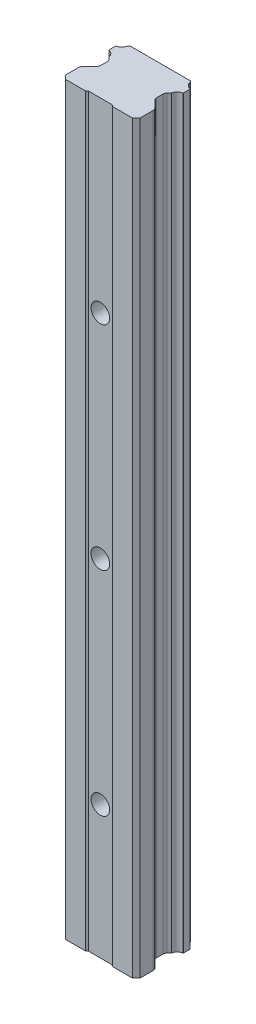
SolidWorks part; units mm, degrees
material "铸造碳钢"
ref_plane "前视基准面" through (0, 0, 0) normal (0, 0, 1) x (1, 0, 0)
ref_plane "上视基准面" through (0, 0, 0) normal (0, 1, 0) x (1, 0, 0)
ref_plane "右视基准面" through (0, 0, 0) normal (1, 0, 0) x (0, 0, -1)
sketch "草图1" plane through (0, 0, 0) normal (0, 1, 0) x (1, 0, 0)
  line L40 (11.7582, -0.4582) -> (11.3, 0)
  line L41 (11.3, 0) -> (-11.3, 0)
  line L42 (-11.3, 0) -> (-11.7582, -0.4582)
  line L43 (-14, -2.848) -> (-14, -5.152)
  line L44 (-11.7582, -7.5418) -> (-10.9393, -8.3607)
  line L45 (-10.5, -9.4213) -> (-10.5, -11.8787)
  line L46 (-10.9393, -12.9393) -> (-13.5607, -15.5607)
  line L47 (-14, -16.6213) -> (-14, -21.5)
  line L48 (-14, -21.5) -> (-12.5, -23)
  line L49 (-12.5, -23) -> (-5, -23)
  line L50 (-5, -23) -> (-4.5, -22.5)
  line L51 (-4.5, -22.5) -> (4.5, -22.5)
  line L52 (4.5, -22.5) -> (5, -23)
  line L53 (5, -23) -> (12.5, -23)
  line L54 (12.5, -23) -> (14, -21.5)
  line L55 (14, -21.5) -> (14, -16.6213)
  line L56 (13.5607, -15.5607) -> (10.9393, -12.9393)
  line L57 (10.5, -11.8787) -> (10.5, -9.4213)
  line L58 (10.9393, -8.3607) -> (11.7582, -7.5418)
  line L59 (14, -5.152) -> (14, -2.848)
  arc A36 (11.7782, -0.4802) -> (11.7582, -0.4582) centre (11.5461, -0.6703) ccw
  arc A37 (-11.7582, -0.4582) -> (-11.7782, -0.4802) centre (-11.5461, -0.6703) ccw
  arc A38 (-13.8926, -2.618) -> (-11.7782, -0.4802) centre (-14.2555, -0.1445) ccw
  arc A39 (-13.8926, -2.618) -> (-14, -2.848) centre (-13.7, -2.848) ccw
  arc A40 (-14, -5.152) -> (-13.8926, -5.382) centre (-13.7, -5.152) ccw
  arc A41 (-11.7782, -7.5198) -> (-13.8926, -5.382) centre (-14.2555, -7.8555) ccw
  arc A42 (-11.7782, -7.5198) -> (-11.7582, -7.5418) centre (-11.5461, -7.3297) ccw
  arc A43 (-10.5, -9.4213) -> (-10.9393, -8.3607) centre (-12, -9.4213) ccw
  arc A44 (-10.9393, -12.9393) -> (-10.5, -11.8787) centre (-12, -11.8787) ccw
  arc A45 (-13.5607, -15.5607) -> (-14, -16.6213) centre (-12.5, -16.6213) ccw
  arc A46 (14, -16.6213) -> (13.5607, -15.5607) centre (12.5, -16.6213) ccw
  arc A47 (10.5, -11.8787) -> (10.9393, -12.9393) centre (12, -11.8787) ccw
  arc A48 (10.9393, -8.3607) -> (10.5, -9.4213) centre (12, -9.4213) ccw
  arc A49 (11.7582, -7.5418) -> (11.7782, -7.5198) centre (11.5461, -7.3297) ccw
  arc A50 (13.8926, -5.382) -> (11.7782, -7.5198) centre (14.2555, -7.8555) ccw
  arc A51 (13.8926, -5.382) -> (14, -5.152) centre (13.7, -5.152) ccw
  arc A52 (14, -2.848) -> (13.8926, -2.618) centre (13.7, -2.848) ccw
  arc A53 (11.7782, -0.4802) -> (13.8926, -2.618) centre (14.2555, -0.1445) ccw
extrude "凸台-拉伸1" add sketch "草图1" along normal blind 280
sketch "草图2" plane through (0, 0, 0) normal (0, 0, -1) x (-1, 0, 0)
  line L0 (-11.3, 0) -> (11.3, 0) construction
  circle A0 centre (0, 50) radius 5.5
  dimension "D1" = 11
  dimension "D2" = 50
extrude "切除-拉伸1" cut sketch "草图2" against normal blind 9
sketch "草图3" plane through (0, 0, 9) normal (0, 0, -1) x (-1, 0, 0)
  circle A0 centre (0, 50) radius 3.5
  dimension "D1" = 7
extrude "切除-拉伸2" cut sketch "草图3" against normal through all
pattern_linear "阵列(线性)1" count 4 spacing 80 along (0, 1, 0) of "切除-拉伸1", "切除-拉伸2"
